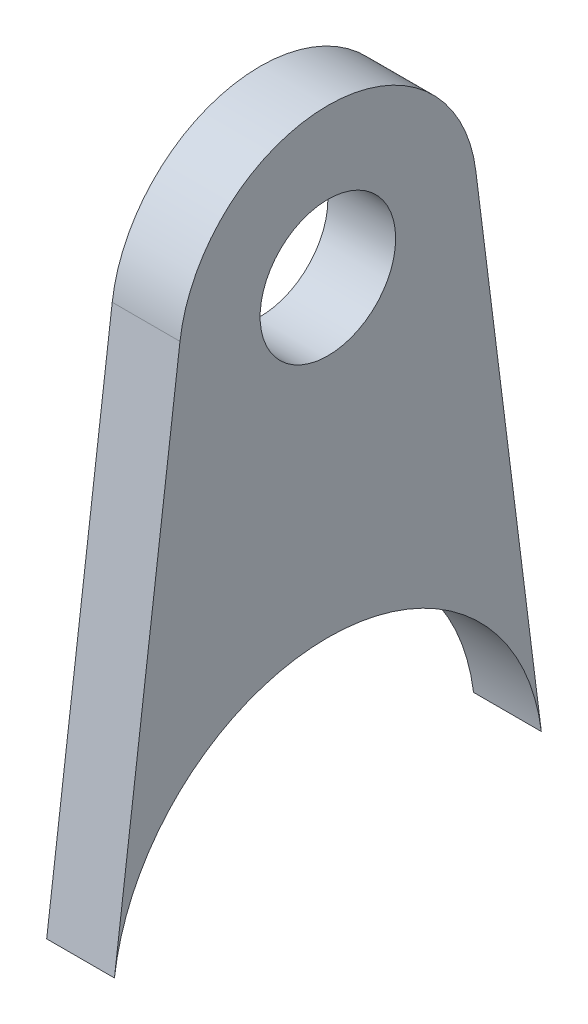
SolidWorks part; units mm, degrees
material "AISI 4130 Steel, normalized at 870C"
ref_plane "Front Plane" through (0, 0, 0) normal (0, 0, 1) x (1, 0, 0)
ref_plane "Top Plane" through (0, 0, 0) normal (0, 1, 0) x (1, 0, 0)
ref_plane "Right Plane" through (0, 0, 0) normal (1, 0, 0) x (0, 0, -1)
sketch "Sketch2" plane through (0, 0, 0) normal (1, 0, 0) x (0, 0, -1)
  line L0 (0, 38.875) -> (0, 15.875) construction
  line L1 (-10.9132, 40.2544) -> (-15.7497, 1.9908)
  line L2 (10.9132, 40.2544) -> (15.7497, 1.9908)
  circle A0 centre (0, 38.875) radius 5
  arc A1 (15.7497, 1.9908) -> (-15.7497, 1.9908) centre (0, 0) ccw
  arc A2 (10.9132, 40.2544) -> (-10.9132, 40.2544) centre (0, 38.875) ccw
  dimension "D1" = 10
  dimension "D2" = 31.75
  dimension "D3" = 23
  dimension "D4" = 22
extrude "Boss-Extrude1" add sketch "Sketch2" along normal mid plane 5
